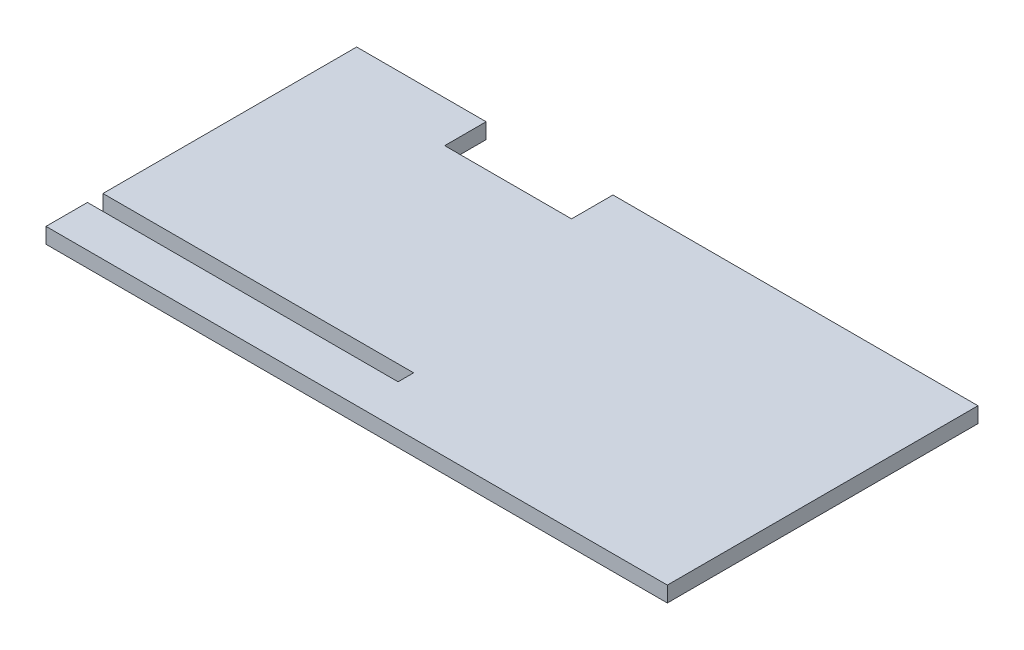
SolidWorks part; units mm, degrees
ref_plane "Front Plane" through (0, 0, 0) normal (0, 0, 1) x (1, 0, 0)
ref_plane "Top Plane" through (0, 0, 0) normal (0, 1, 0) x (1, 0, 0)
ref_plane "Right Plane" through (0, 0, 0) normal (1, 0, 0) x (0, 0, -1)
sketch "Sketch1" plane through (0, 0, 0) normal (0, 1, 0) x (1, 0, 0)
  line L0 (-60, -9) -> (0, -9)
  line L1 (-60, -20) -> (60, -20)
  line L2 (-60, -20) -> (-60, 40)
  line L3 (-60, 40) -> (60, 40)
  line L4 (60, -20) -> (60, 40)
  line L7 (0, -9) -> (0, -12)
  line L8 (0, -12) -> (-60, -12)
  line L9 (-35, 40) -> (-35, 32)
  line L10 (-35, 32) -> (-10.5, 32)
  line L11 (-10.5, 32) -> (-10.5, 40)
  point P0 (0, 0)
  dimension "D1" = 8
  dimension "D2" = 120
  dimension "D3" = 9
  dimension "D4" = 3
  dimension "D5" = 8
  dimension "D6" = 24.5
  dimension "D7" = 25
  dimension "D8" = 40
extrude "Boss-Extrude1" add sketch "Sketch1" along normal blind 3 contours L7 L8 L2 L1 L4 L3 L0
